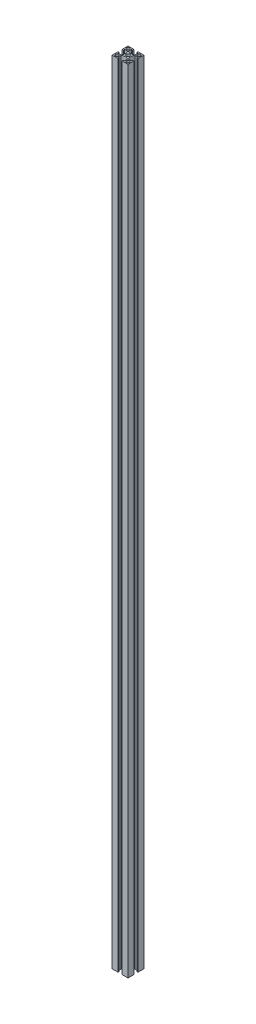
SolidWorks part; units mm, degrees
ref_plane "정면" through (0, 0, 0) normal (0, 0, 1) x (1, 0, 0)
ref_plane "윗면" through (0, 0, 0) normal (0, 1, 0) x (1, 0, 0)
ref_plane "우측면" through (0, 0, 0) normal (1, 0, 0) x (0, 0, -1)
sketch "스케치2" plane through (0, 0, 0) normal (0, 1, 0) x (1, 0, 0)
  line L1 (-10, 10) -> (10, 10)
  line L2 (-10, 10) -> (-10, -10)
  line L3 (-10, -10) -> (10, -10)
  line L4 (10, 10) -> (10, -10)
  line L5 (-10, 10) -> (10, -10) construction
  line L6 (-10, -10) -> (10, 10) construction
  point P0 (0, 0)
  dimension "D1" = 20
  dimension "D2" = 20
extrude "20201000" add sketch "스케치2" along normal blind 1000
sketch "스케치1" plane through (0, 0, 0) normal (0, 1, 0) x (1, 0, 0)
  line L0 (-10, 8.5) -> (-8.5, 8.5)
  line L1 (-10, 10) -> (10, 10)
  line L2 (-10, 10) -> (-10, -10)
  line L3 (-10, -10) -> (10, -10)
  line L4 (10, 10) -> (10, -10)
  line L5 (-10, 10) -> (10, -10) construction
  line L6 (-10, -10) -> (10, 10) construction
  line L7 (-7, 7) -> (7, 7)
  line L8 (-7, 7) -> (-7, -7)
  line L9 (-7, -7) -> (7, -7)
  line L10 (7, 7) -> (7, -7)
  line L11 (-7, 7) -> (7, -7) construction
  line L12 (-7, -7) -> (7, 7) construction
  line L13 (0, 0) -> (0, 10) construction
  line L14 (2.65, 10) -> (2.65, 8.5)
  line L15 (-2.65, 10) -> (-2.65, 8.5)
  line L17 (-4.15, 8.5) -> (-4.15, 4.74)
  line L18 (4.15, 8.5) -> (4.15, 4.74)
  line L19 (8.5, 8.5) -> (10, 8.5)
  line L20 (-4.15, 8.5) -> (-2.65, 8.5)
  line L21 (2.65, 8.5) -> (4.15, 8.5)
  arc A1 (-4.15, 4.74) -> (4.15, 4.74) centre (0, 10) ccw
  point P0 (0, 0)
  point P6 (0, 0)
  point P27 (0, 0)
  point P28 (0, 0)
  point P29 (0, 9.5756)
  dimension "D6" = 6.7
  dimension "D1" = 20
  dimension "D2" = 14
  dimension "D3" = 1.5
  dimension "D4" = 2.65
  dimension "D5" = 2.65
  dimension "D7" = 4.15
  dimension "D8" = 4.15
extrude "홈컷" cut sketch "스케치1" against normal through all and the other way through all contours L17 A1 L18 L7 | L21 L14 L1 L15 L20 L17 L7 L18
sketch "스케치3" plane through (0, 0, 0) normal (1, 0, 0) x (0, 0, -1)
  line L0 (0, 0) -> (0, 200) construction
  line L1 (-10, 0) -> (10, 0) construction
  dimension "D1" = 200
pattern_circular "원형 패턴1" count 4 over 360 about axis through (0, 0, 0) along (0, 1, 0) of "홈컷"
sketch "스케치4" plane through (0, 0, 0) normal (0, -1, 0) x (1, 0, 0)
  line L1 (-7, 7) -> (7, 7)
  line L2 (-7, 7) -> (-7, -7)
  line L3 (-7, -7) -> (7, -7)
  line L4 (7, 7) -> (7, -7)
  line L5 (-7, 7) -> (7, -7) construction
  line L6 (-7, -7) -> (7, 7) construction
  circle A0 centre (-7, 7) radius 2
  circle A1 centre (7, 7) radius 2
  circle A2 centre (7, -7) radius 2
  circle A3 centre (-7, -7) radius 2
  circle A4 centre (0, 0) radius 2.15
  point P0 (0, 0)
  dimension "D2" = 4
  dimension "D3" = 4.3
  dimension "D1" = 14
extrude "컷-돌출4" cut sketch "스케치4" against normal blind 1000 contours L4 A1 L1 | L1 A1 L4 | A4 | L4 A2 L3 | L3 A2 L4 | L3 A3 L2 | L2 A3 L3 | L1 A0 L2 | L2 A0 L1
